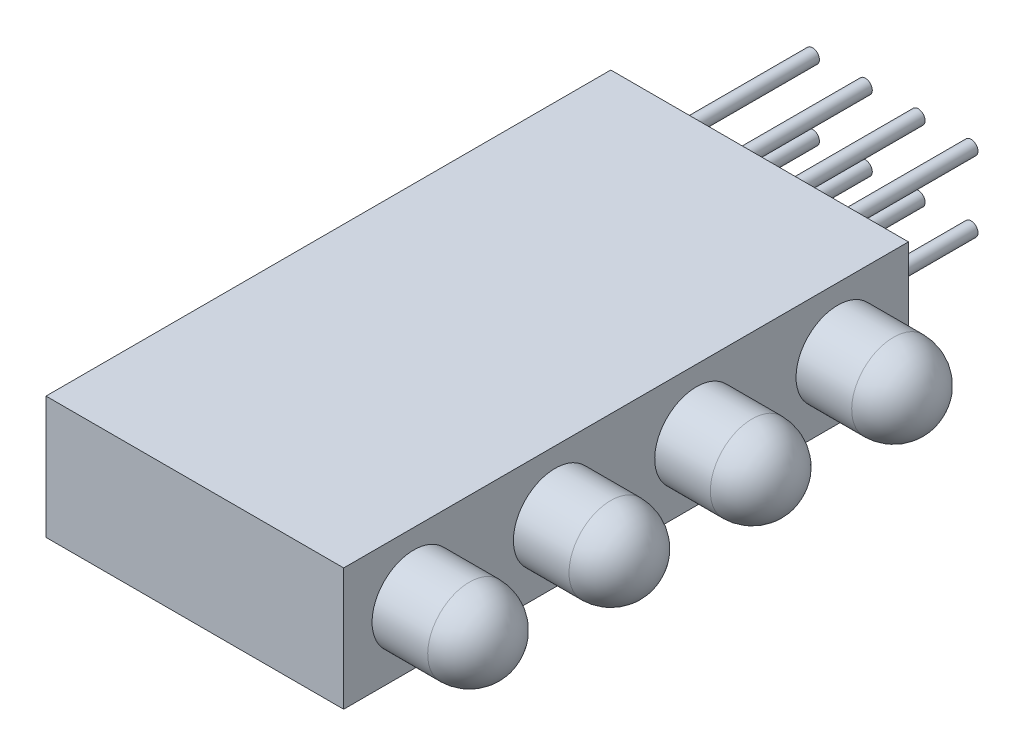
SolidWorks part; units mm, degrees
ref_plane "前视基准面" through (0, 0, 0) normal (0, 0, 1) x (1, 0, 0)
ref_plane "上视基准面" through (0, 0, 0) normal (0, 1, 0) x (1, 0, 0)
ref_plane "右视基准面" through (0, 0, 0) normal (1, 0, 0) x (0, 0, -1)
sketch "草图1" plane through (0, 0, 0) normal (0, 0, 1) x (1, 0, 0)
  line L0 (11.6837, 0) -> (-12.2492, 0) construction
  line L1 (-5.35, 2.2) -> (5.35, 2.2)
  line L2 (-5.35, 2.2) -> (-5.35, -2.2)
  line L3 (-5.35, -2.2) -> (5.35, -2.2)
  line L4 (5.35, 2.2) -> (5.35, -2.2)
  line L5 (0, -6.0381) -> (0, 4.4432) construction
  dimension "D1" = 4.4
  dimension "D2" = 10.7
extrude "凸台-拉伸1" add sketch "草图1" along normal blind 20.3
sketch "草图2" plane through (0, 0, 0) normal (0, 0, -1) x (-1, 0, 0)
  line L0 (-7.0359, 0) -> (7.4664, 0) construction
  line L1 (-4.5376, 1.27) -> (7.9685, 1.27) construction
  line L2 (-5.35, -2.2) -> (-5.35, 2.2) construction
  line L3 (-4.5376, -1.27) -> (7.9685, -1.27) construction
  circle A0 centre (-2.6, 1.27) radius 0.25
  circle A1 centre (-0.7, 1.27) radius 0.25
  circle A2 centre (1.2, 1.27) radius 0.25
  circle A3 centre (3.1, 1.27) radius 0.25
  circle A4 centre (3.1, -1.27) radius 0.25
  circle A5 centre (1.2, -1.27) radius 0.25
  circle A6 centre (-0.7, -1.27) radius 0.25
  circle A7 centre (-2.6, -1.27) radius 0.25
  dimension "D2" = 0.5
  dimension "D3" = 4
  dimension "D1" = 2.75
  dimension "D4" = 2.54
extrude "凸台-拉伸2" add sketch "草图2" along normal blind 5
sketch "草图3" plane through (5.35, 0, 0) normal (1, 0, 0) x (0, 0, -1)
  line L0 (5.1241, 0) -> (-22.1916, 0) construction
  line L1 (0, -2.2) -> (0, 2.2) construction
  circle A0 centre (-2.54, 0) radius 1.5
  circle A1 centre (-7.62, 0) radius 1.5
  circle A2 centre (-12.7, 0) radius 1.5
  circle A3 centre (-17.78, 0) radius 1.5
  dimension "D1" = 3
  dimension "D2" = 2.54
  dimension "D3" = 4
extrude "凸台-拉伸3" add sketch "草图3" along normal blind 3.5
fillet "圆角1" radius 1.5 4 edges at (8.85, 1.5, 17.78) (8.85, 1.5, 2.54) (8.85, 1.5, 7.62) (8.85, 1.5, 12.7)
